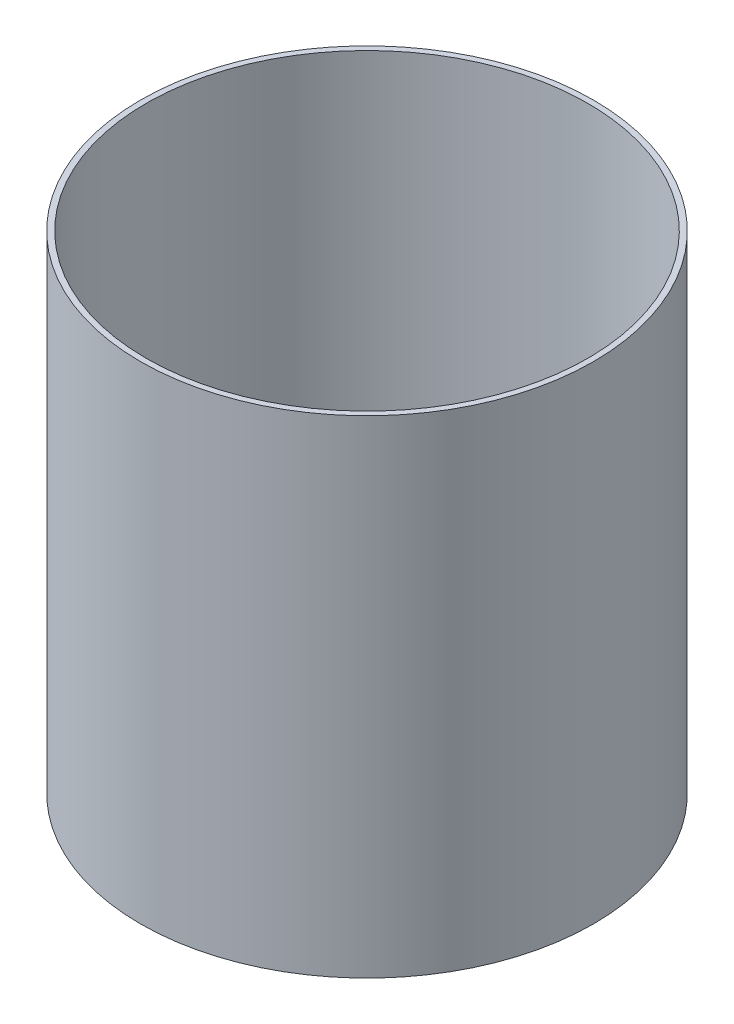
SolidWorks part; units mm, degrees
ref_plane "前视基准面" through (0, 0, 0) normal (0, 0, 1) x (1, 0, 0)
ref_plane "上视基准面" through (0, 0, 0) normal (0, 1, 0) x (1, 0, 0)
ref_plane "右视基准面" through (0, 0, 0) normal (1, 0, 0) x (0, 0, -1)
sketch "草图1" plane through (0, 0, 0) normal (0, 1, 0) x (1, 0, 0)
  circle A0 centre (0, 0) radius 195
  circle A1 centre (0, 0) radius 200
  dimension "D1" = 390
  dimension "D2" = 400
extrude "凸台-拉伸1" add sketch "草图1" along normal blind 430
